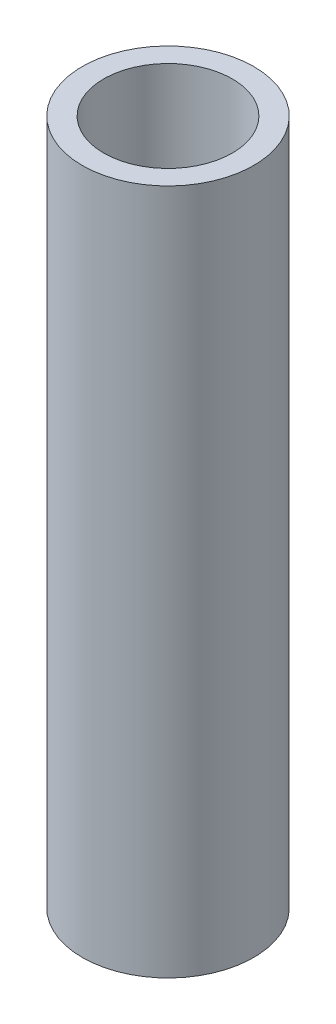
SolidWorks part; units mm, degrees
ref_plane "前视基准面" through (0, 0, 0) normal (0, 0, 1) x (1, 0, 0)
ref_plane "上视基准面" through (0, 0, 0) normal (0, 1, 0) x (1, 0, 0)
ref_plane "右视基准面" through (0, 0, 0) normal (1, 0, 0) x (0, 0, -1)
sketch "草图1" plane through (0, 0, 0) normal (0, 1, 0) x (1, 0, 0)
  circle A0 centre (0, 0) radius 1
  circle A1 centre (0, 0) radius 0.75
  dimension "D1" = 2
  dimension "D2" = 1.5
extrude "凸台-拉伸1" add sketch "草图1" along normal blind 8
